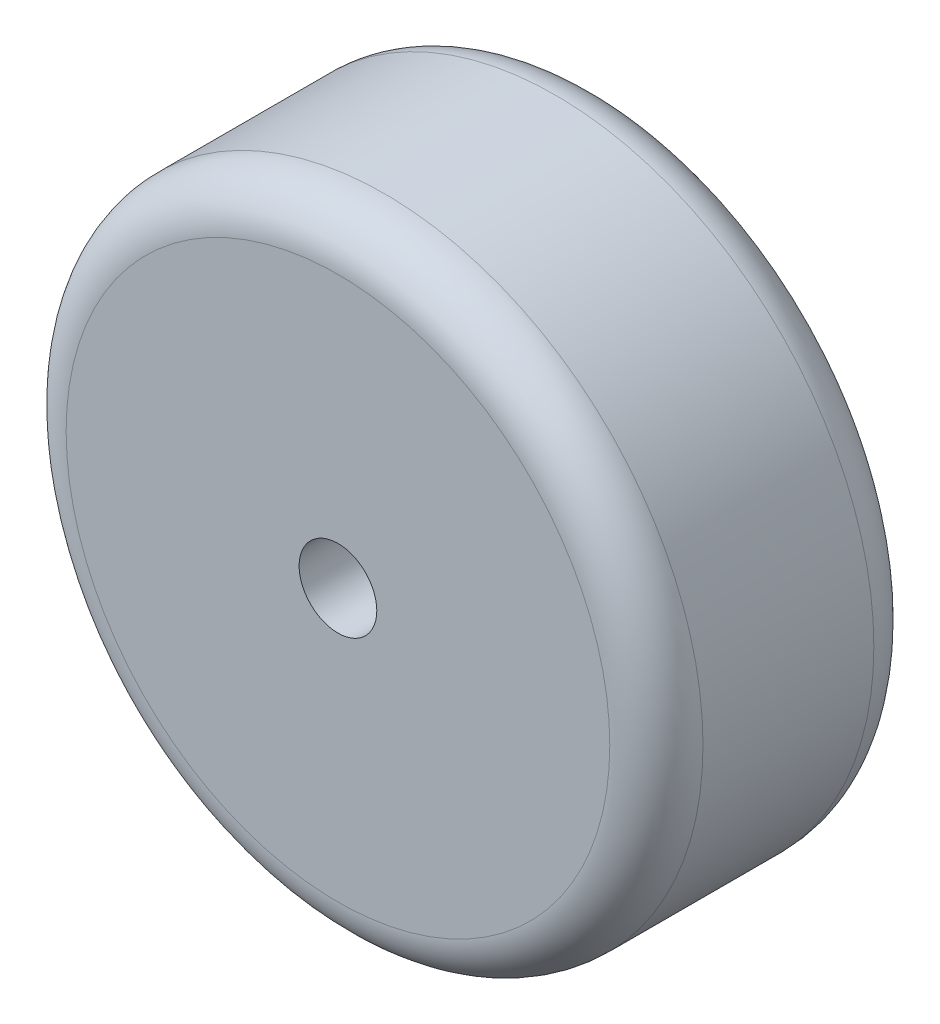
SolidWorks part; units mm, degrees
ref_plane "Front Plane" through (0, 0, 0) normal (0, 0, 1) x (1, 0, 0)
ref_plane "Top Plane" through (0, 0, 0) normal (0, 1, 0) x (1, 0, 0)
ref_plane "Right Plane" through (0, 0, 0) normal (1, 0, 0) x (0, 0, -1)
sketch "草图1" plane through (0, 0, 0) normal (0, 0, 1) x (1, 0, 0)
  circle A0 centre (0, 0) radius 20.5
  dimension "D1" = 41
extrude "凸台-拉伸1" add sketch "草图1" along normal blind 17
sketch "草图2" plane through (0, 0, 17) normal (0, 0, 1) x (1, 0, 0)
  circle A0 centre (0, 0) radius 2.5
  dimension "D1" = 5
extrude "切除-拉伸1" cut sketch "草图2" against normal through all
fillet "圆角1" radius 3 2 edges at (20.5, 0, 0) (20.5, 0, 17)
